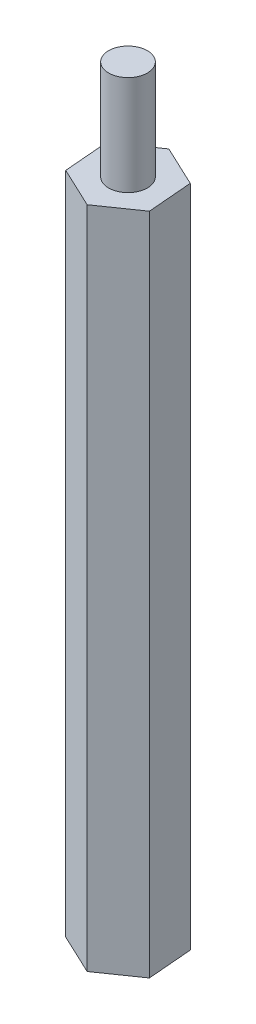
SolidWorks part; units mm, degrees
ref_plane "Plan de face" through (0, 0, 0) normal (0, 0, 1) x (1, 0, 0)
ref_plane "Plan de dessus" through (0, 0, 0) normal (0, 1, 0) x (1, 0, 0)
ref_plane "Plan de droite" through (0, 0, 0) normal (1, 0, 0) x (0, 0, -1)
sketch "Esquisse1" plane through (0, 0, 0) normal (0, 1, 0) x (1, 0, 0)
  line L1 (3.6558, -1.7229) -> (3.32, 2.3046)
  line L2 (3.32, 2.3046) -> (-0.3359, 4.0275)
  line L3 (-0.3359, 4.0275) -> (-3.6558, 1.7229)
  line L4 (-3.6558, 1.7229) -> (-3.32, -2.3046)
  line L5 (-3.32, -2.3046) -> (0.3359, -4.0275)
  line L6 (0.3359, -4.0275) -> (3.6558, -1.7229)
  circle A0 centre (0, 0) radius 3.5 construction
  point P1 (0, 0)
  dimension "D1" = 3.5
extrude "Boss.-Extru.1" add sketch "Esquisse1" along normal blind 60
sketch "Esquisse2" plane through (0, 0, 0) normal (0, -1, 0) x (1, 0, 0)
  circle A0 centre (0, 0) radius 2
  dimension "D1" = 4
extrude "Enlèv. mat.-Extru.1" cut sketch "Esquisse2" against normal blind 10
sketch "Esquisse3" plane through (0, 60, 0) normal (0, 1, 0) x (1, 0, 0)
  circle A0 centre (0, 0) radius 1.75
  dimension "D1" = 3.5
extrude "Boss.-Extru.2" add sketch "Esquisse3" along normal blind 9
